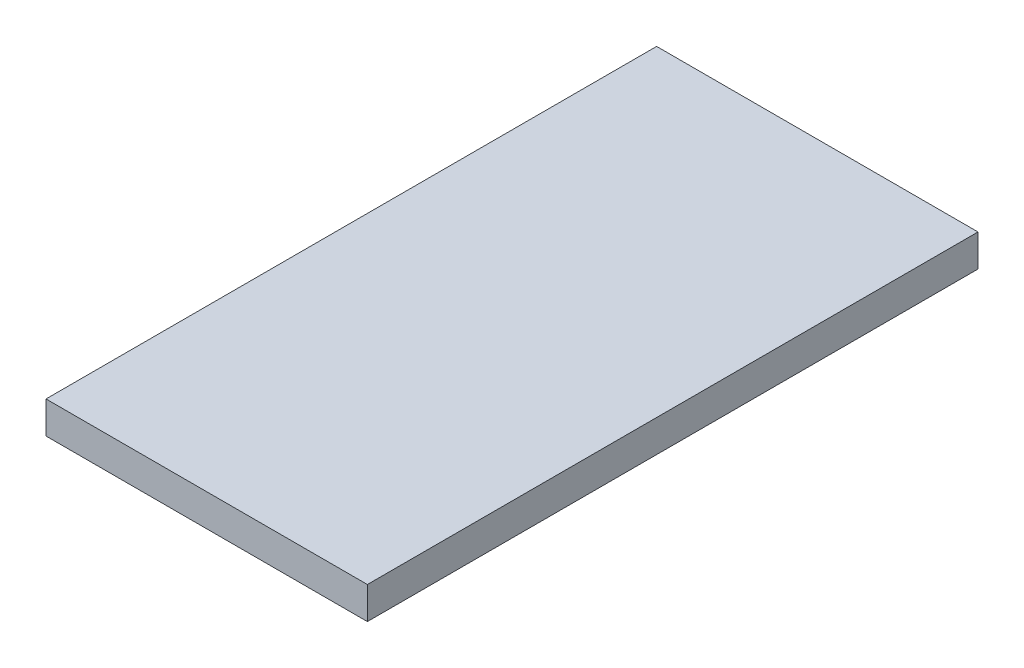
SolidWorks part; units mm, degrees
ref_plane "Front Plane" through (0, 0, 0) normal (0, 0, 1) x (1, 0, 0)
ref_plane "Top Plane" through (0, 0, 0) normal (0, 1, 0) x (1, 0, 0)
ref_plane "Right Plane" through (0, 0, 0) normal (1, 0, 0) x (0, 0, -1)
sketch "Sketch1" plane through (0, 0, 0) normal (0, 1, 0) x (1, 0, 0)
  line L1 (0, 0) -> (50.8, 0)
  line L2 (0, 0) -> (0, 96.52)
  line L3 (0, 96.52) -> (50.8, 96.52)
  line L4 (50.8, 0) -> (50.8, 96.52)
  dimension "D1" = 50.8
  dimension "D2" = 96.52
extrude "Boss-Extrude1" add sketch "Sketch1" along normal blind 5.08
